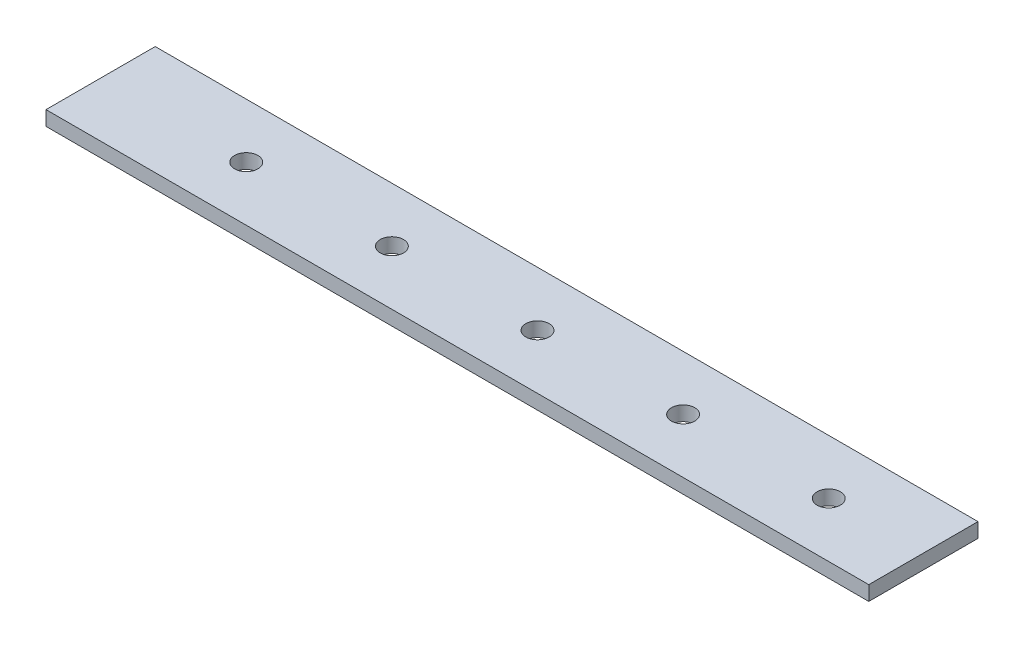
SolidWorks part; units mm, degrees
ref_plane "Plan de face" through (0, 0, 0) normal (0, 0, 1) x (1, 0, 0)
ref_plane "Plan de dessus" through (0, 0, 0) normal (0, 1, 0) x (1, 0, 0)
ref_plane "Plan de droite" through (0, 0, 0) normal (1, 0, 0) x (0, 0, -1)
sketch "Esquisse1" plane through (0, 0, 0) normal (0, 1, 0) x (1, 0, 0)
  line L0 (0, 0) -> (0, 15)
  line L1 (0, 15) -> (113, 15)
  line L2 (113, 15) -> (113, 0)
  line L3 (113, 0) -> (0, 0)
  circle A0 centre (20, 7.5) radius 1.6
  circle A1 centre (40, 7.5) radius 1.6
  circle A2 centre (60, 7.5) radius 1.6
  circle A3 centre (80, 7.5) radius 1.6
  circle A4 centre (100, 7.5) radius 1.6
  dimension "D3" = 3.2
  dimension "D1" = 15
  dimension "D2" = 113
  dimension "D4" = 7.5
  dimension "D5" = 20
  dimension "D6" = 5
extrude "Boss.-Extru.1" add sketch "Esquisse1" along normal blind 2
